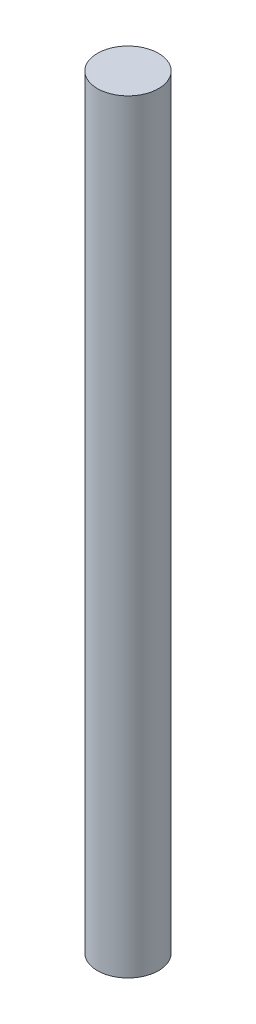
SolidWorks part; units mm, degrees
material "玻璃"
ref_plane "前视基准面" through (0, 0, 0) normal (0, 0, 1) x (1, 0, 0)
ref_plane "上视基准面" through (0, 0, 0) normal (0, 1, 0) x (1, 0, 0)
ref_plane "右视基准面" through (0, 0, 0) normal (1, 0, 0) x (0, 0, -1)
other "Configuration Table"
sketch "草图1" plane through (0, 0, 0) normal (0, 1, 0) x (1, 0, 0)
  circle A0 centre (0, 0) radius 4
extrude "凸台-拉伸1" add sketch "草图1" along normal blind 100
